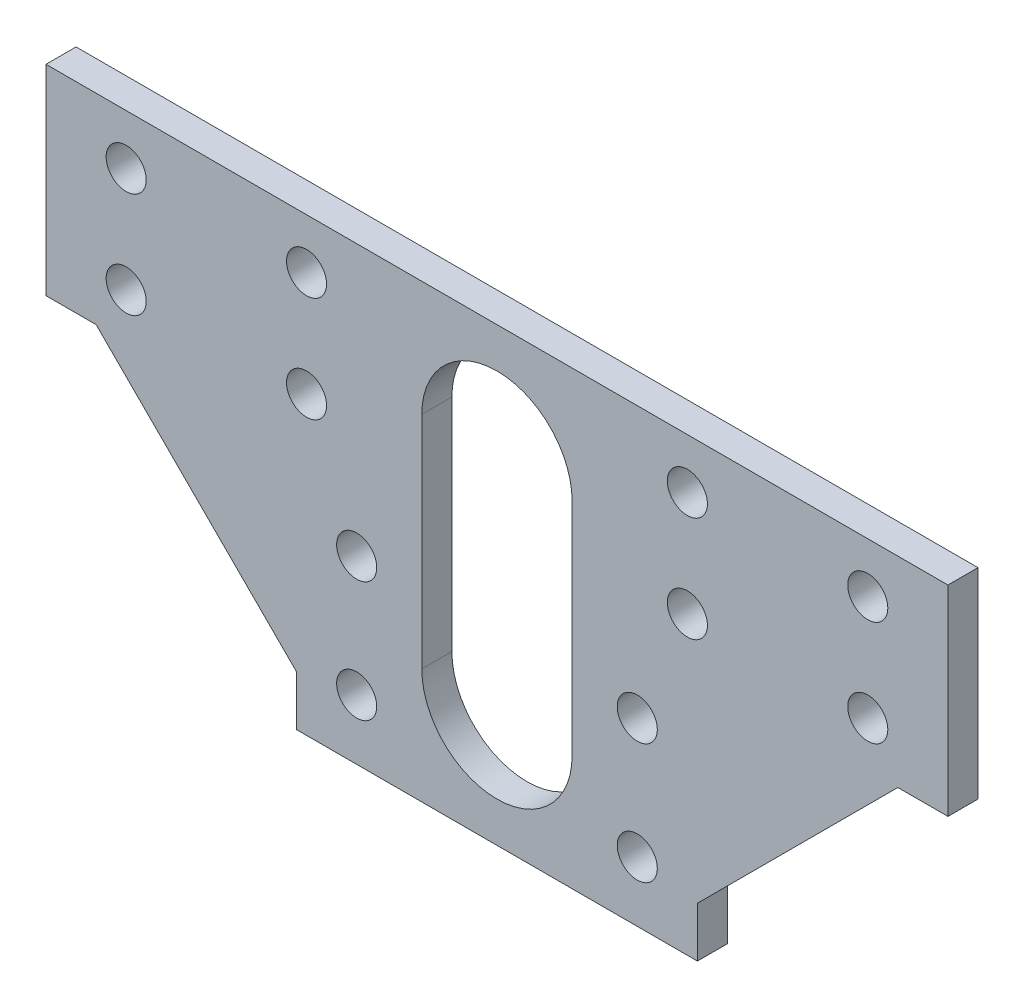
SolidWorks part; units mm, degrees
material "Thornel VCB-20 碳布"
ref_plane "前视基准面" through (0, 0, 0) normal (0, 0, 1) x (1, 0, 0)
ref_plane "上视基准面" through (0, 0, 0) normal (0, 1, 0) x (1, 0, 0)
ref_plane "右视基准面" through (0, 0, 0) normal (1, 0, 0) x (0, 0, -1)
other "Configuration Table"
sketch "草图1" plane through (0, 0, 0) normal (0, 0, 1) x (1, 0, 0)
  line L0 (0, 0) -> (90, 0)
  line L1 (90, 0) -> (90, -20)
  line L2 (90, -20) -> (85, -20)
  line L3 (85, -20) -> (65, -40)
  line L4 (65, -40) -> (65, -45)
  line L5 (65, -45) -> (25, -45)
  line L6 (25, -45) -> (25, -40)
  line L7 (25, -40) -> (5, -20)
  line L8 (5, -20) -> (0, -20)
  line L9 (0, -20) -> (0, 0)
  line L10 (5, -20) -> (85, -20) construction
  line L11 (65, -40) -> (65, -20) construction
  line L12 (25, -40) -> (25, -20) construction
  dimension "D1" = 40
  dimension "D2" = 20
  dimension "D3" = 45
  dimension "D4" = 25
  dimension "D5" = 25
  dimension "D6" = 25
  dimension "D7" = 20
extrude "凸台-拉伸1" add sketch "草图1" along normal blind 3
sketch "草图2" plane through (0, 0, 3) normal (0, 0, 1) x (1, 0, 0)
  line L0 (45, -11.5) -> (45, -33.5) construction
  line L1 (8, -5) -> (82, -5) construction
  line L2 (8, -5) -> (8, -15.5) construction
  line L3 (8, -15.5) -> (82, -15.5) construction
  line L4 (82, -5) -> (82, -15.5) construction
  line L5 (31, -27) -> (59, -27) construction
  line L6 (31, -27) -> (31, -39) construction
  line L7 (31, -39) -> (59, -39) construction
  line L8 (59, -27) -> (59, -39) construction
  line L9 (52.5, -11.5) -> (52.5, -33.5)
  line L10 (0, 0) -> (0, -20)
  line L11 (0, -20) -> (5, -20)
  line L12 (5, -20) -> (25, -40)
  line L13 (25, -40) -> (25, -45)
  line L14 (25, -45) -> (65, -45)
  line L15 (65, -45) -> (65, -40)
  line L16 (65, -40) -> (85, -20)
  line L17 (85, -20) -> (90, -20)
  line L18 (90, -20) -> (90, 0)
  line L19 (90, 0) -> (0, 0)
  line L20 (0, 0) -> (0, -20) construction
  line L21 (0, -20) -> (5, -20) construction
  line L22 (5, -20) -> (25, -40) construction
  line L23 (25, -40) -> (25, -45) construction
  line L24 (25, -45) -> (65, -45) construction
  line L25 (65, -45) -> (65, -40) construction
  line L26 (65, -40) -> (85, -20) construction
  line L27 (85, -20) -> (90, -20) construction
  line L28 (90, -20) -> (90, 0) construction
  line L29 (90, 0) -> (0, 0) construction
  line L30 (37.5, -11.5) -> (37.5, -33.5)
  circle A0 centre (82, -5) radius 2
  circle A1 centre (82, -15.5) radius 2
  circle A2 centre (64, -15.5) radius 2
  circle A3 centre (64, -5) radius 2
  circle A4 centre (26, -5) radius 2
  circle A5 centre (26, -15.5) radius 2
  circle A6 centre (8, -5) radius 2
  circle A7 centre (8, -15.5) radius 2
  circle A8 centre (31, -27) radius 2
  circle A9 centre (31, -39) radius 2
  circle A10 centre (59, -27) radius 2
  circle A11 centre (59, -39) radius 2
  arc A12 (52.5, -11.5) -> (37.5, -11.5) centre (45, -11.5) ccw
  arc A13 (37.5, -33.5) -> (52.5, -33.5) centre (45, -33.5) ccw
  point P36 (45, -22.5)
  point P41 (40.8457, -14.8416)
  dimension "D2" = 4
  dimension "D16" = 7.5
  dimension "D3" = 8
  dimension "D4" = 8
  dimension "D5" = 18
  dimension "D6" = 18
  dimension "D7" = 18
  dimension "D8" = 18
  dimension "D9" = 5
  dimension "D10" = 10.5
  dimension "D11" = 6
  dimension "D12" = 6
  dimension "D13" = 6
  dimension "D14" = 12
  dimension "D15" = 20
  dimension "D17" = 23
  dimension "D18" = 22
  dimension "D1" = 0
extrude "切除-拉伸1" cut sketch "草图2" against normal blind 3
